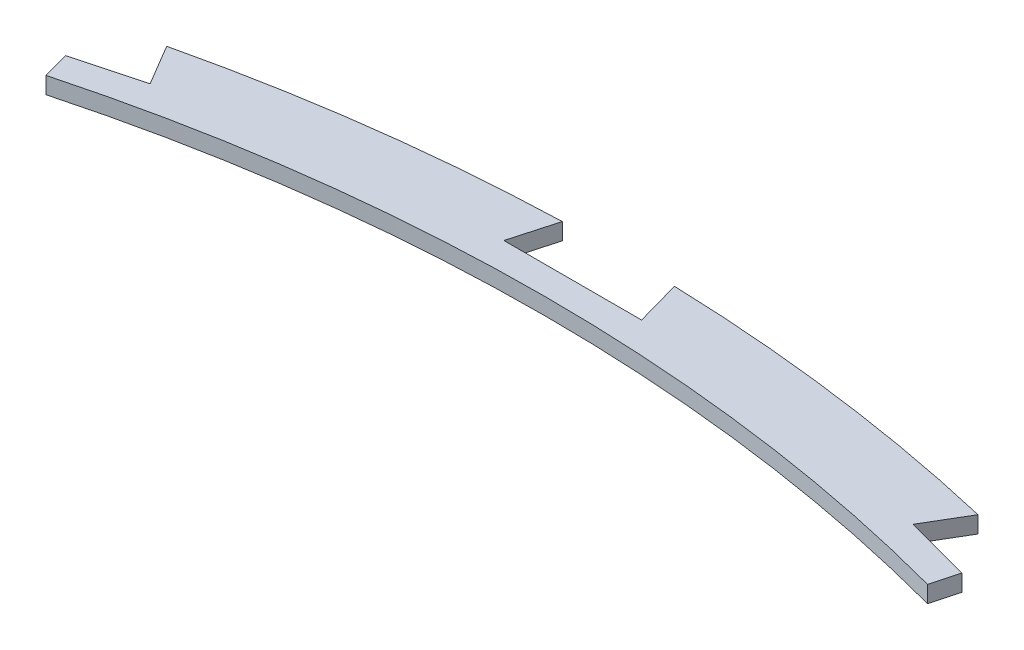
SolidWorks part; units mm, degrees
ref_plane "Front Plane" through (0, 0, 0) normal (0, 0, 1) x (1, 0, 0)
ref_plane "Top Plane" through (0, 0, 0) normal (0, 1, 0) x (1, 0, 0)
ref_plane "Right Plane" through (0, 0, 0) normal (1, 0, 0) x (0, 0, -1)
sketch "Sketch1" plane through (0, 0, 0) normal (0, 1, 0) x (1, 0, 0)
  line L0 (0, 0) -> (-280.8187, 1048.0295)
  line L1 (-280.8187, 1085) -> (280.8187, 1085) construction
  line L2 (-280.8187, 1085) -> (-280.8187, 785) construction
  line L3 (-280.8187, 785) -> (280.8187, 785) construction
  line L4 (280.8187, 1085) -> (280.8187, 785) construction
  line L5 (0, 0) -> (280.8187, 1048.0295)
  line L6 (0, 1020) -> (0, 0) construction
  line L7 (-37, 930) -> (37, 930)
  line L8 (37, 930) -> (30.1331, 954.5245)
  line L9 (955, 0) -> (1000, 0) construction
  line L10 (1000, 0) -> (1045, 0) construction
  line L11 (-37, 930) -> (-30.1331, 954.5245)
  line L12 (-240.7017, 898.311) -> (-204.9625, 907.8873)
  line L13 (-204.9625, 907.8873) -> (-217.9427, 929.7989)
  line L14 (240.7017, 898.311) -> (204.9625, 907.8873)
  line L15 (204.9625, 907.8873) -> (217.9427, 929.7989)
  circle A0 centre (0, 0) radius 1085
  circle A1 centre (0, 0) radius 1045
  circle A2 centre (0, 0) radius 955
  circle A3 centre (0, 0) radius 915
  circle A6 centre (0, 0) radius 1065 construction
  circle A7 centre (0, 0) radius 935 construction
  circle A12 centre (0, 0) radius 1032.5 construction
  circle A15 centre (0, 0) radius 1000 construction
  point P12 (0, 785)
  point P17 (30, 955)
  point P25 (0, 930)
  point P27 (-218.1944, 930.2237)
  dimension "D8" = 2000
  dimension "D1" = 300
  dimension "D3" = 40
  dimension "D4" = 40
  dimension "D5" = 20
  dimension "D6" = 20
  dimension "D7" = 170
  dimension "D2" = 15
  dimension "D13" = 15
  dimension "D14" = 12.5
  dimension "D9" = 37
  dimension "D10" = 30
  dimension "D11" = 25
  dimension "D12" = 930
  dimension "D15" = 37
  dimension "D16" = 25
  dimension "D17" = 30
  dimension "D18" = 930
extrude "Boss-Extrude1" add sketch "Sketch1" along normal blind 9 contours A3 L5 A2 L8 L7 L11 L0
equation "\"D12@Sketch1\"=1910/2-25"
equation "\"D18@Sketch1\"=1910/2-25"
